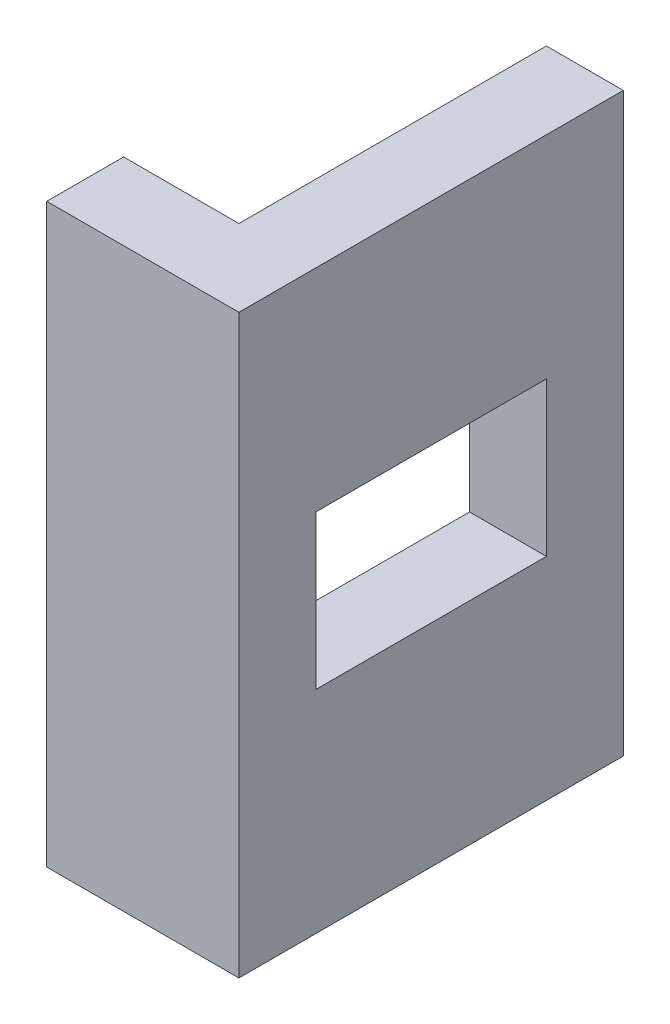
SolidWorks part; units mm, degrees
ref_plane "Front Plane" through (0, 0, 0) normal (0, 0, 1) x (1, 0, 0)
ref_plane "Top Plane" through (0, 0, 0) normal (0, 1, 0) x (1, 0, 0)
ref_plane "Right Plane" through (0, 0, 0) normal (1, 0, 0) x (0, 0, -1)
sketch "Sketch1" plane through (0, 0, 0) normal (0, 0, 1) x (1, 0, 0)
  line L5 (-2.5, -7.5) -> (2.5, -7.5)
  line L6 (-2.5, -7.5) -> (-2.5, 7.5)
  line L7 (-2.5, 7.5) -> (2.5, 7.5)
  line L8 (2.5, -7.5) -> (2.5, 7.5)
  line L9 (-2.5, -7.5) -> (2.5, 7.5) construction
  line L10 (-2.5, 7.5) -> (2.5, -7.5) construction
  point P0 (0, 0)
  point P1 (0, 0)
  dimension "D1" = 15
  dimension "D2" = 5
extrude "Boss-Extrude1" add sketch "Sketch1" along normal mid plane 10
sketch "Sketch4" plane through (0, 7.5, 0) normal (0, 1, 0) x (1, 0, 0)
  line L1 (-2.5, 5) -> (0.5, 5)
  line L2 (-2.5, 5) -> (-2.5, -3)
  line L3 (-2.5, -3) -> (0.5, -3)
  line L4 (0.5, 5) -> (0.5, -3)
  dimension "D1" = 8
  dimension "D2" = 3
extrude "Cut-Extrude3" cut sketch "Sketch4" against normal up to surface (15 mm away) up to face at (0, -7.5, 0)
sketch "Sketch5" plane through (0.5, 0, 0) normal (-1, 0, 0) x (0, 0, 1)
  line L5 (3, -7.5) -> (3, 7.5) construction
  line L9 (-3, -2) -> (3, -2)
  line L10 (-3, -2) -> (-3, 2)
  line L11 (-3, 2) -> (3, 2)
  line L12 (3, -2) -> (3, 2)
  dimension "D1" = 6
  dimension "D3" = 2
  dimension "D2" = 4
extrude "Cut-Extrude5" cut sketch "Sketch5" against normal up to surface (2 mm away)
